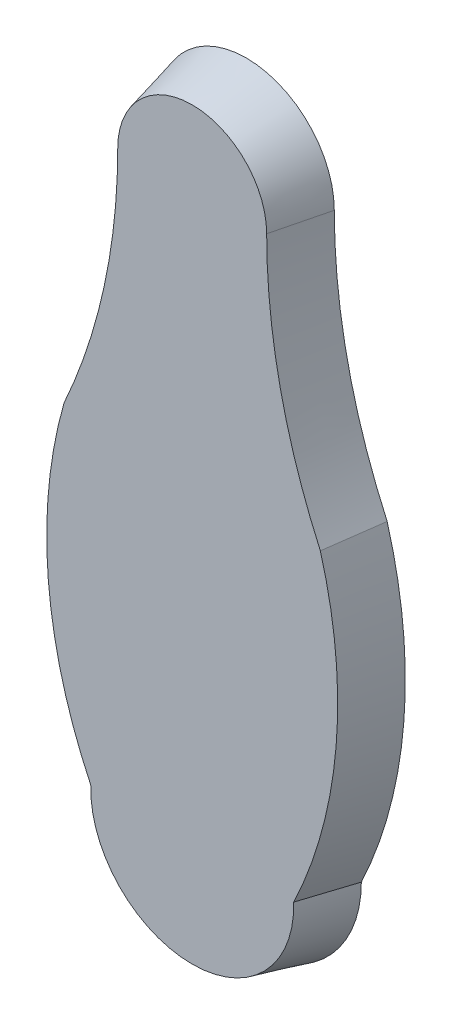
SolidWorks part; units mm, degrees
ref_plane "Front Plane" through (0, 0, 0) normal (0, 0, 1) x (1, 0, 0)
ref_plane "Top Plane" through (0, 0, 0) normal (0, 1, 0) x (1, 0, 0)
ref_plane "Right Plane" through (0, 0, 0) normal (1, 0, 0) x (0, 0, -1)
sketch "Sketch1" plane through (0, 0, 0) normal (0, 0, 1) x (1, 0, 0)
  line L0 (0, 210) -> (0, 0) construction
  line L1 (0, -55) -> (0, 55) construction
  arc A0 (-42.5, 0) -> (42.5, 0) centre (0, 0) ccw
  arc A1 (32.5, 210) -> (-32.5, 210) centre (0, 210) ccw
  arc A2 (-32.5, 210) -> (-52.0405, 120.1973) centre (-248.6247, 210) cw
  arc A3 (-52.0405, 120.1973) -> (-42.5, 0) centre (112.2923, 72.7637) ccw
  arc A4 (52.0405, 120.1973) -> (42.5, 0) centre (-112.2923, 72.7637) cw
  arc A5 (32.5, 210) -> (52.0405, 120.1973) centre (248.6247, 210) ccw
  dimension "D1" = 85
  dimension "D2" = 65
  dimension "D3" = 210
extrude "Boss-Extrude1" add sketch "Sketch1" along normal blind 20 draft 14 contours A2 A3 A0 A4 A5 A1
